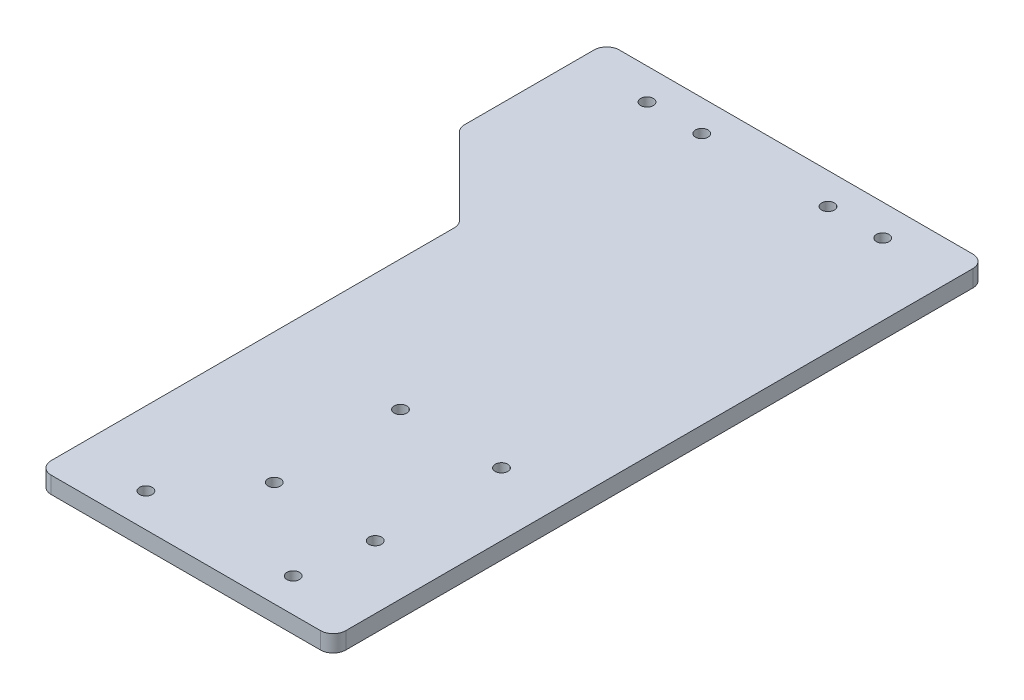
SolidWorks part; units mm, degrees
ref_plane "前视基准面" through (0, 0, 0) normal (0, 0, 1) x (1, 0, 0)
ref_plane "上视基准面" through (0, 0, 0) normal (0, 1, 0) x (1, 0, 0)
ref_plane "右视基准面" through (0, 0, 0) normal (1, 0, 0) x (0, 0, -1)
sketch "草图1" plane through (0, 0, 0) normal (0, 1, 0) x (1, 0, 0)
  line L0 (0, 0) -> (60, 0)
  line L1 (60, 0) -> (60, 155)
  line L2 (60, 155) -> (-30, 155)
  line L4 (0, 90) -> (0, 0)
  line L6 (0, 90) -> (-30, 120)
  line L7 (-30, 120) -> (-30, 155)
  dimension "D1" = 60
  dimension "D2" = 155
  dimension "D3" = 90
  dimension "D4" = 90
  dimension "D5" = 135
extrude "凸台-拉伸1" add sketch "草图1" along normal blind 4
sketch "草图2" plane through (0, 4, 0) normal (0, 1, 0) x (1, 0, 0)
  line L0 (60, 0) -> (60, 155) construction
  line L1 (0, 0) -> (60, 0) construction
  circle A0 centre (45, 25) radius 1.5
  circle A1 centre (21, 25) radius 1.5
  circle A2 centre (45, 55) radius 1.5
  circle A3 centre (21, 55) radius 1.5
  dimension "D1" = 24
  dimension "D2" = 24
  dimension "D3" = 30
  dimension "D4" = 15
  dimension "D5" = 25
extrude "切除-拉伸1" cut sketch "草图2" against normal blind 4
sketch "草图3" plane through (0, 4, 0) normal (0, 1, 0) x (1, 0, 0)
  line L0 (15, 164.4826) -> (15, 101.7411) construction
  circle A0 centre (30, 147.5907) radius 1.5
  circle A1 centre (43, 147.5907) radius 1.5
  circle A2 centre (-13, 147.5907) radius 1.5
  circle A3 centre (0, 147.5907) radius 1.5
  dimension "D1" = 15
  dimension "D2" = 28
extrude "切除-拉伸2" cut sketch "草图3" against normal blind 4
sketch "草图5" plane through (0, 4, 0) normal (0, 1, 0) x (1, 0, 0)
  line L0 (0, 0) -> (-10, 0)
  line L1 (-10, 0) -> (-10, 100)
  line L2 (-10, 100) -> (0, 90)
  line L3 (-30, 120) -> (0, 90) construction
  line L4 (0, 90) -> (0, 0)
  dimension "D1" = 10
extrude "凸台-拉伸2" add sketch "草图5" against normal up to surface (4 mm away) up to face at (43, 0, -146.0907)
fillet "圆角2" radius 3 6 edges at (60, 2, 0) (-10, 2, 0) (-10, 2, -100) (-30, 2, -120) (-30, 2, -155) (60, 2, -155)
sketch "草图6" plane through (0, 4, 0) normal (0, 1, 0) x (1, 0, 0)
  line L1 (-7, 0) -> (57, 0) construction
  line L2 (60, 3) -> (60, 152) construction
  circle A0 centre (7.5, 8) radius 1.5
  circle A1 centre (42.5, 8) radius 1.5
  dimension "D1" = 35
  dimension "D2" = 17.5
  dimension "D4" = 8
  dimension "D5" = 8
extrude "切除-拉伸3" cut sketch "草图6" against normal through all
